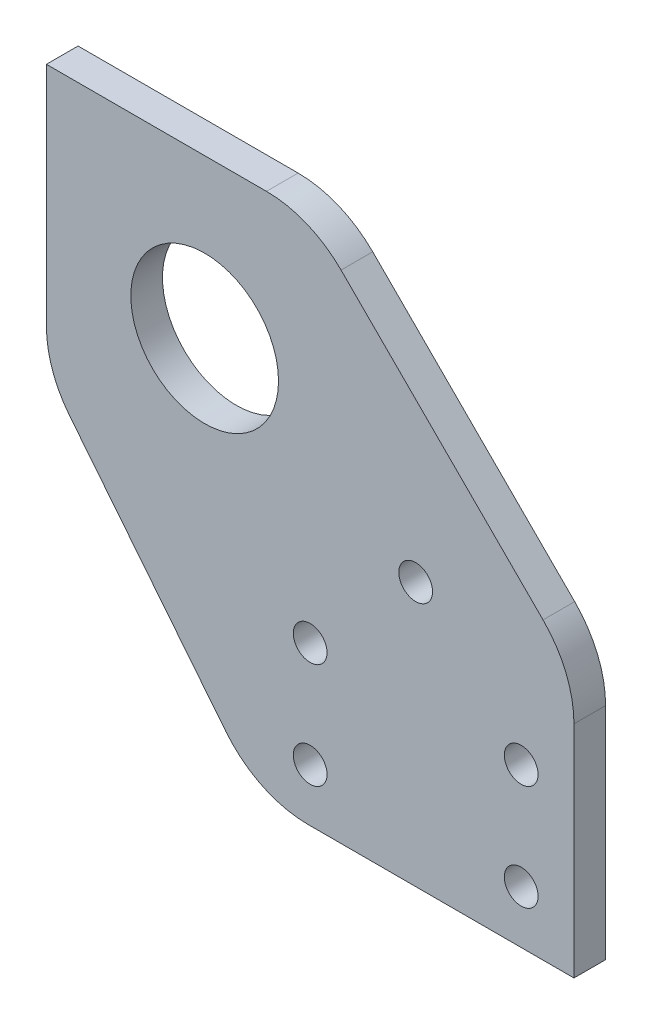
SolidWorks part; units mm, degrees
ref_plane "前视基准面" through (0, 0, 0) normal (0, 0, 1) x (1, 0, 0)
ref_plane "上视基准面" through (0, 0, 0) normal (0, 1, 0) x (1, 0, 0)
ref_plane "右视基准面" through (0, 0, 0) normal (1, 0, 0) x (0, 0, -1)
other "Configuration Table"
sketch "草图1" plane through (0, 0, 0) normal (0, 0, 1) x (1, 0, 0)
  line L1 (0, 0) -> (50, 0)
  line L2 (0, 0) -> (0, -50)
  line L3 (0, -50) -> (50, -50)
  line L4 (50, 0) -> (50, -50)
  dimension "D1" = 50
  dimension "D2" = 50
extrude "凸台-拉伸1" add sketch "草图1" along normal blind 3
sketch "草图2" plane through (0, 0, 3) normal (0, 0, 1) x (1, 0, 0)
  line L0 (50, 0) -> (0, 0) construction
  line L1 (50, -50) -> (50, 0) construction
  line L2 (0, -15) -> (50, -15) construction
  line L3 (0, 0) -> (0, -50) construction
  line L6 (40, 0) -> (40, -50) construction
  line L8 (0, -50) -> (50, -50) construction
  line L9 (35, 0) -> (35, -50) construction
  line L10 (40, -40) -> (50, -40) construction
  circle A0 centre (15, -15) radius 7
  circle A6 centre (45, -45) radius 1.6
  circle A7 centre (45, -35) radius 1.6
  circle A8 centre (25, -35) radius 1.6
  circle A9 centre (25, -45) radius 1.6
  circle A10 centre (35, -25) radius 1.6
  point P28 (0, 0)
  dimension "D1" = 14
  dimension "D4" = 10
  dimension "D7" = 5
  dimension "D11" = 25
  dimension "D6" = 5
  dimension "D8" = 3.2
  dimension "D10" = 3.2
  dimension "D2" = 15
  dimension "D3" = 15
  dimension "D5" = 5
  dimension "D9" = 10
extrude "切除-拉伸1" cut sketch "草图2" against normal through all
sketch "草图3" plane through (0, 0, 3) normal (0, 0, 1) x (1, 0, 0)
  line L0 (0, -25) -> (20, -50)
  line L1 (0, 0) -> (0, -50) construction
  line L2 (0, -50) -> (50, -50) construction
  line L3 (20, -50) -> (0, -50)
  line L4 (0, -50) -> (0, -25)
  line L5 (25, 0) -> (50, 0)
  line L6 (50, 0) -> (0, 0) construction
  line L7 (50, 0) -> (50, -25)
  line L8 (50, -50) -> (50, 0) construction
  line L9 (50, -25) -> (25, 0)
  dimension "D1" = 25
  dimension "D2" = 25
  dimension "D3" = 20
extrude "切除-拉伸2" cut sketch "草图3" against normal through all
fillet "圆角1" radius 10 4 edges at (20, -50, 1.5) (0, -25, 1.5) (50, -25, 1.5) (25, 0, 1.5)
